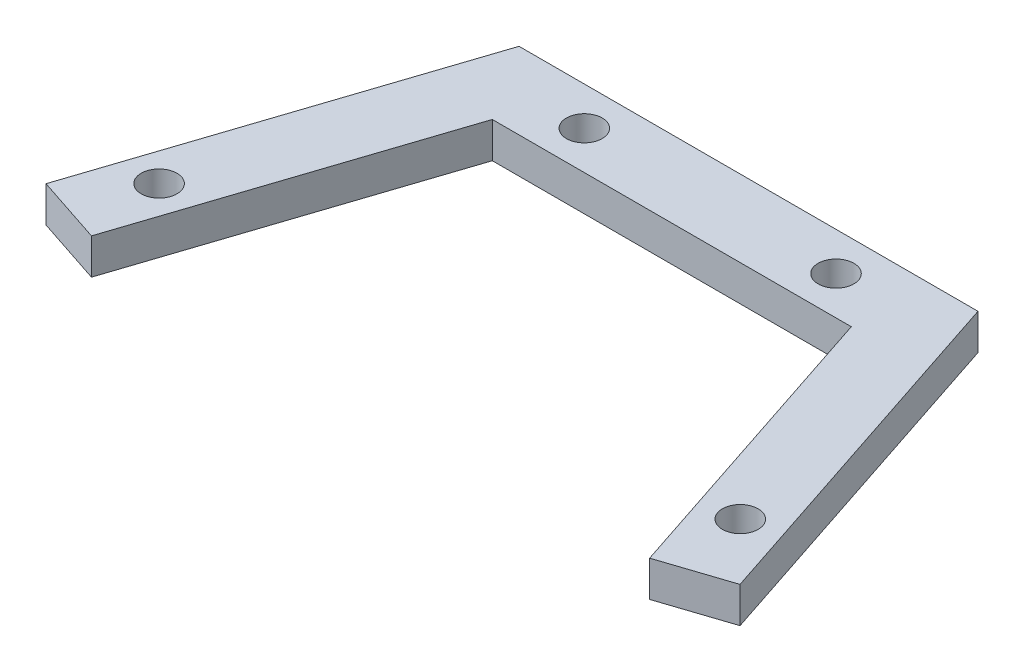
SolidWorks part; units mm, degrees
material "6061-T6 (SS)"
ref_plane "Front Plane" through (0, 0, 0) normal (0, 0, 1) x (1, 0, 0)
ref_plane "Top Plane" through (0, 0, 0) normal (0, 1, 0) x (1, 0, 0)
ref_plane "Right Plane" through (0, 0, 0) normal (1, 0, 0) x (0, 0, -1)
sketch "Sketch1" plane through (0, 0, 0) normal (0, 1, 0) x (1, 0, 0)
  line L0 (0, 4.29) -> (0, -4.29) construction
  line L1 (-20.075, -4.29) -> (20.075, -4.29)
  line L2 (-20.075, -4.29) -> (-20.075, 4.29) construction
  line L3 (-20.075, 4.29) -> (20.075, 4.29)
  line L4 (20.075, -4.29) -> (20.075, 4.29) construction
  line L5 (-20.075, -4.29) -> (20.075, 4.29) construction
  line L6 (-20.075, 4.29) -> (20.075, -4.29) construction
  line L7 (-20.075, 0) -> (20.075, 0) construction
  line L8 (-14.075, 0) -> (-14.075, -29.13) construction
  line L9 (-14.075, -29.13) -> (-32.5, -29.13) construction
  line L10 (14.075, -29.13) -> (32.5, -29.13) construction
  line L11 (14.075, 0) -> (14.075, -29.13) construction
  line L12 (-20.075, 4.29) -> (-25.6643, 4.29)
  line L13 (-25.6643, 4.29) -> (-38.809, -35.4701)
  line L14 (-38.809, -35.4701) -> (-31.2133, -37.9812)
  line L15 (-31.2133, -37.9812) -> (-20.075, -4.29)
  line L16 (-32.5, -29.13) -> (-36.2978, -27.8744) construction
  line L17 (-32.5, -29.13) -> (-28.7022, -30.3856) construction
  line L18 (31.2133, -37.9812) -> (20.075, -4.29)
  line L19 (32.5, -29.13) -> (28.7022, -30.3856) construction
  line L20 (32.5, -29.13) -> (36.2978, -27.8744) construction
  line L21 (38.809, -35.4701) -> (31.2133, -37.9812)
  line L22 (25.6643, 4.29) -> (38.809, -35.4701)
  line L23 (20.075, 4.29) -> (25.6643, 4.29)
  circle A0 centre (14.075, 0) radius 2
  circle A1 centre (-14.075, 0) radius 2
  circle A4 centre (-32.5, -29.13) radius 2
  circle A5 centre (32.5, -29.13) radius 2
  point P0 (0, 0)
  dimension "D2" = 4
  dimension "D3" = 28.15
  dimension "D5" = 4
  dimension "D7" = 65
  dimension "D8" = 8
  dimension "D1" = 40.15
  dimension "D4" = 8.58
  dimension "D6" = 29.13
  dimension "D9" = 8
extrude "Boss-Extrude1" add sketch "Sketch1" along normal mid plane 4
